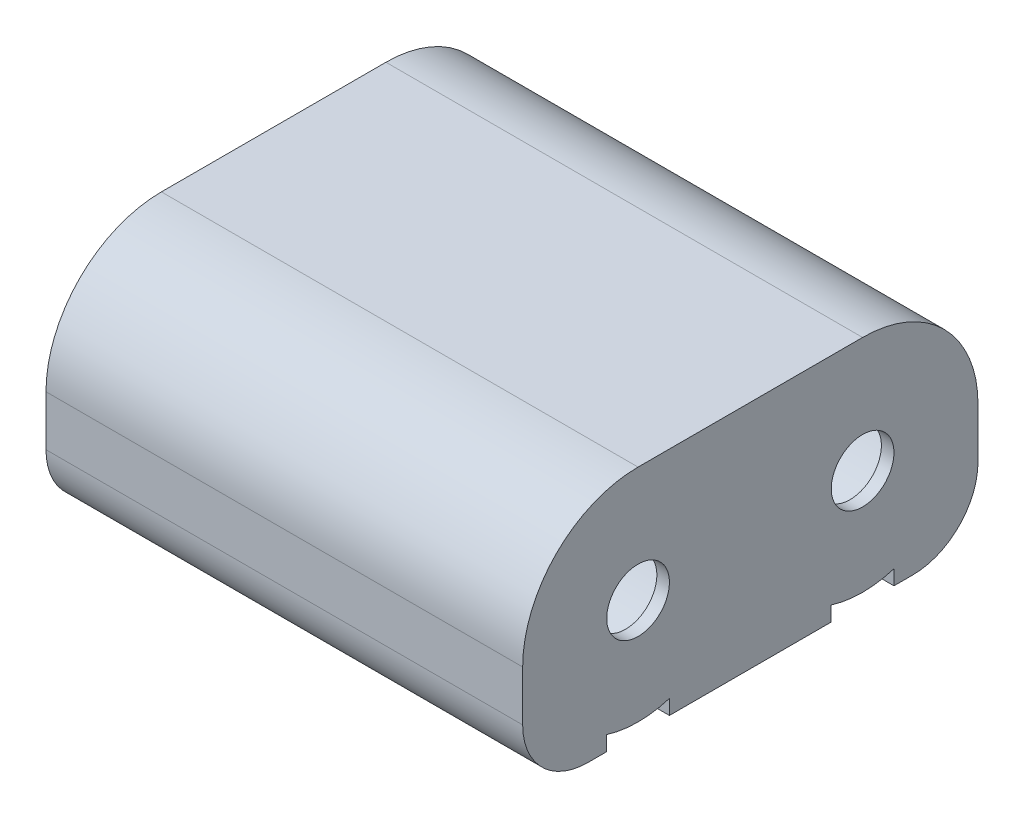
SolidWorks part; units mm, degrees
ref_plane "Спереди" through (0, 0, 0) normal (0, 0, 1) x (1, 0, 0)
ref_plane "Сверху" through (0, 0, 0) normal (0, 1, 0) x (1, 0, 0)
ref_plane "Справа" through (0, 0, 0) normal (1, 0, 0) x (0, 0, -1)
sketch "Эскиз1" plane through (0, 0, 0) normal (1, 0, 0) x (0, 0, -1)
  line L0 (0, -999.8279) -> (0, 49000.1721) construction
  line L1 (-1000, 0) -> (49000, 0) construction
  line L2 (-8.95, -9.2) -> (8.95, -9.2)
  line L3 (-8.95, -8.4) -> (-5.1977, -8.4) construction
  line L4 (-5.1977, -8.4) -> (-1.93, -8.4) construction
  line L5 (-1.93, -8.4) -> (1.93, -8.4)
  line L6 (5.1977, -8.4) -> (8.95, -8.4) construction
  line L7 (1.93, -8.4) -> (5.1977, -8.4) construction
  line L8 (-1.93, 8.4) -> (1.93, 8.4)
  line L9 (-8.95, 9.2) -> (8.95, 9.2)
  line L10 (-18.15, -4) -> (-18.15, 0)
  line L11 (18.15, -4) -> (18.15, 0)
  line L12 (12.95, -9.2) -> (8.95, -9.2)
  line L13 (-12.95, -9.2) -> (-8.95, -9.2)
  arc A2 (-1.93, -8.4) -> (-2.6183, -6.6745) centre (-1.93, -7.4) cw
  arc A3 (1.93, -8.4) -> (2.6183, -6.6745) centre (1.93, -7.4) ccw
  circle A14 centre (-8.95, 0) radius 8.35 construction
  circle A15 centre (-8.95, 0) radius 8.35 construction
  circle A16 centre (-8.95, 0) radius 8.4
  arc A17 (-2.6183, -6.6745) -> (-0.8775, -4.4129) centre (-8.95, 0) ccw
  circle A18 centre (8.95, 0) radius 8.35 construction
  circle A19 centre (8.95, 0) radius 8.35 construction
  circle A20 centre (8.95, 0) radius 8.4
  arc A21 (18.15, 0) -> (8.95, 9.2) centre (8.95, 0) ccw
  arc A22 (-5.1977, -8.4) -> (-2.6183, -6.6745) centre (-8.95, 0) ccw construction
  circle A23 centre (-8.95, 0) radius 9.2 construction
  arc A24 (-8.95, -9.2) -> (-5.1977, -8.4) centre (-8.95, 0) ccw construction
  arc A25 (5.1977, -8.4) -> (8.95, -9.2) centre (8.95, 0) ccw construction
  circle A26 centre (8.95, 0) radius 9.2 construction
  arc A27 (2.6183, -6.6745) -> (5.1977, -8.4) centre (8.95, 0) ccw construction
  arc A28 (-1.93, 8.4) -> (-2.6183, 6.6745) centre (-1.93, 7.4) ccw
  arc A29 (1.93, 8.4) -> (2.6183, 6.6745) centre (1.93, 7.4) cw
  arc A30 (-2.6183, 6.6745) -> (-8.95, 9.2) centre (-8.95, 0) ccw construction
  arc A31 (-8.95, 9.2) -> (-18.15, 0) centre (-8.95, 0) ccw
  arc A32 (8.95, 9.2) -> (2.6183, 6.6745) centre (8.95, 0) ccw construction
  arc A33 (2.6183, 6.6745) -> (0.8775, 4.4129) centre (8.95, 0) ccw
  arc A34 (0.8775, -4.4129) -> (-0.8775, -4.4129) centre (0, -4.8926) ccw
  arc A35 (0.8775, 4.4129) -> (-0.8775, 4.4129) centre (0, 4.8926) cw
  arc A36 (0, 2.1301) -> (-0.8775, 4.4129) centre (-8.95, 0) ccw construction
  arc A37 (-0.8775, 4.4129) -> (-2.6183, 6.6745) centre (-8.95, 0) ccw
  arc A38 (0.8775, 4.4129) -> (0, 2.1301) centre (8.95, 0) ccw construction
  arc A39 (0.8775, -4.4129) -> (2.6183, -6.6745) centre (8.95, 0) ccw
  arc A40 (0, 2.1301) -> (0.8775, -4.4129) centre (8.95, 0) ccw construction
  arc A41 (-0.8775, -4.4129) -> (0, 2.1301) centre (-8.95, 0) ccw construction
  arc A42 (-12.95, -9.2) -> (-18.15, -4) centre (-12.95, -4) cw
  arc A43 (12.95, -9.2) -> (18.15, -4) centre (12.95, -4) ccw
  arc A44 (-18.15, 0) -> (-8.95, -9.2) centre (-8.95, 0) ccw construction
  arc A45 (8.95, -9.2) -> (18.15, 0) centre (8.95, 0) ccw construction
  dimension "D3" = 4
  dimension "D5" = 1
  dimension "D1" = 0.05
  dimension "D2" = 0.8
extrude "Бобышка-Вытянуть1" add sketch "Эскиз1" along normal mid plane 37
sketch "Эскиз2" plane through (18.5, 0, 0) normal (1, 0, 0) x (0, 0, -1)
  line L4 (18.15, -4) -> (18.15, 0) construction
  line L5 (-12.95, -9.2) -> (12.95, -9.2) construction
  line L6 (-18.15, 0) -> (-18.15, -4) construction
  line L7 (8.95, 9.2) -> (-8.95, 9.2) construction
  line L8 (18.15, -4) -> (18.15, 0)
  line L9 (-12.95, -9.2) -> (12.95, -9.2)
  line L10 (-18.15, 0) -> (-18.15, -4)
  line L11 (8.95, 9.2) -> (-8.95, 9.2)
  circle A4 centre (-8.95, 0) radius 2.5
  circle A5 centre (8.95, 0) radius 2.5
  arc A7 (18.15, 0) -> (8.95, 9.2) centre (8.95, 0) ccw construction
  arc A8 (12.95, -9.2) -> (18.15, -4) centre (12.95, -4) ccw construction
  arc A9 (-18.15, -4) -> (-12.95, -9.2) centre (-12.95, -4) ccw construction
  arc A10 (-8.95, 9.2) -> (-18.15, 0) centre (-8.95, 0) ccw construction
  arc A11 (18.15, 0) -> (8.95, 9.2) centre (8.95, 0) ccw
  arc A12 (12.95, -9.2) -> (18.15, -4) centre (12.95, -4) ccw
  arc A13 (-18.15, -4) -> (-12.95, -9.2) centre (-12.95, -4) ccw
  arc A14 (-8.95, 9.2) -> (-18.15, 0) centre (-8.95, 0) ccw
  dimension "D1" = 5
extrude "Бобышка-Вытянуть2" add sketch "Эскиз2" along normal blind 1
sketch "Эскиз3" plane through (0, -9.2, 0) normal (0, -1, 0) x (1, 0, 0)
  line L0 (0, -1000) -> (0, 49000) construction
  line L1 (-1000, 0) -> (49000, 0) construction
  circle A0 centre (-10, 0) radius 1.5
  circle A1 centre (10, 0) radius 1.5
  dimension "D1" = 3
  dimension "D2" = 20
ref_plane "Плоскость1" through (-10, 0, 0) normal (1, 0, 0) x (0, 0, -1)
sketch "Эскиз5" plane through (-10, 0, 0) normal (1, 0, 0) x (0, 0, -1)
  line L1 (-1.93, -8.4) -> (1.93, -8.4)
  line L2 (-1.93, -8.4) -> (1.93, -8.4)
  arc A5 (-2.6183, -6.6745) -> (-1.93, -8.4) centre (-1.93, -7.4) ccw
  arc A6 (1.93, -8.4) -> (2.6183, -6.6745) centre (1.93, -7.4) ccw
  arc A7 (0.8775, -4.4129) -> (2.6183, -6.6745) centre (8.95, 0) ccw
  arc A8 (0.8775, -4.4129) -> (-0.8775, -4.4129) centre (0, -4.8926) ccw
  arc A9 (-2.6183, -6.6745) -> (-0.8775, -4.4129) centre (-8.95, 0) ccw
  arc A10 (-2.6183, -6.6745) -> (-1.93, -8.4) centre (-1.93, -7.4) ccw
  arc A11 (1.93, -8.4) -> (2.6183, -6.6745) centre (1.93, -7.4) ccw
  arc A12 (0.8775, -4.4129) -> (2.6183, -6.6745) centre (8.95, 0) ccw
  arc A13 (0.8775, -4.4129) -> (-0.8775, -4.4129) centre (0, -4.8926) ccw
  arc A14 (-2.6183, -6.6745) -> (-0.8775, -4.4129) centre (-8.95, 0) ccw
  dimension "D1" = 0
extrude "Бобышка-Вытянуть4" add sketch "Эскиз5" along normal mid plane 6
mirror "Зеркальное отражение1" about plane through (0, 0, 0) normal (1, 0, 0) of "Бобышка-Вытянуть4"
extrude "Вырез-Вытянуть1" cut sketch "Эскиз3" against normal blind 5
sketch "Эскиз6" plane through (-18.5, 0, 0) normal (-1, 0, 0) x (0, 0, 1)
  line L0 (10.45, -7.1953) -> (10.45, -16.35) construction
  line L1 (7.45, -16.35) -> (7.45, -7.1953) construction
  line L2 (-7.45, -7.1953) -> (-7.45, -16.35) construction
  line L3 (-10.45, -16.35) -> (-10.45, -7.1953) construction
  line L4 (10.45, -7.1953) -> (10.45, -8.265) construction
  line L5 (7.45, -8.265) -> (7.45, -7.1953) construction
  line L6 (-7.45, -8.265) -> (-7.45, -9.2) construction
  line L7 (-10.45, -9.2) -> (-10.45, -8.265) construction
  line L8 (12.95, -9.2) -> (-12.95, -9.2) construction
  line L9 (11.45, -9.2) -> (6.45, -9.2)
  line L10 (-7.45, -9.2) -> (-7.45, -16.35) construction
  line L11 (-10.45, -16.35) -> (-10.45, -9.2) construction
  line L12 (7.45, -16.35) -> (7.45, -9.2) construction
  line L13 (10.45, -9.2) -> (10.45, -16.35) construction
  line L14 (-6.45, -8.0194) -> (-6.45, -9.2)
  line L15 (-11.45, -9.2) -> (-11.45, -8.0194)
  line L16 (6.45, -9.2) -> (6.45, -8.0194)
  line L17 (11.45, -8.0194) -> (11.45, -9.2)
  line L18 (-11.45, -8.0194) -> (-11.45, -7.1953) construction
  line L19 (-11.45, -9.2) -> (-11.45, -7.1953) construction
  line L20 (-10.45, -8.265) -> (-10.45, -7.1953) construction
  line L21 (-10.45, -9.2) -> (-10.45, -7.1953) construction
  line L22 (-7.45, -7.1953) -> (-7.45, -8.265) construction
  line L23 (-7.45, -7.1953) -> (-7.45, -9.2) construction
  line L24 (-6.45, -7.1953) -> (-6.45, -8.0194) construction
  line L25 (-6.45, -7.1953) -> (-6.45, -9.2) construction
  line L26 (-11.45, -9.2) -> (-12.95, -9.2) construction
  line L27 (6.45, -9.2) -> (-6.45, -9.2) construction
  line L28 (-6.45, -9.2) -> (-11.45, -9.2)
  line L29 (12.95, -9.2) -> (11.45, -9.2) construction
  line L30 (10.45, -8.265) -> (10.45, -9.2) construction
  line L31 (10.45, -7.1953) -> (10.45, -9.2) construction
  line L32 (7.45, -9.2) -> (7.45, -8.265) construction
  line L33 (7.45, -9.2) -> (7.45, -7.1953) construction
  line L34 (11.45, -7.1953) -> (11.45, -8.0194) construction
  line L35 (11.45, -7.1953) -> (11.45, -9.2) construction
  line L36 (6.45, -8.0194) -> (6.45, -7.1953) construction
  line L37 (6.45, -9.2) -> (6.45, -7.1953) construction
  circle A0 centre (-8.95, 0) radius 8.4 construction
  arc A1 (-11.45, -8.0194) -> (-6.45, -8.0194) centre (-8.95, 0) ccw
  circle A2 centre (8.95, 0) radius 8.4 construction
  arc A3 (6.45, -8.0194) -> (11.45, -8.0194) centre (8.95, 0) ccw
  arc A4 (-6.45, -8.0194) -> (-11.45, -8.0194) centre (-8.95, 0) ccw construction
  arc A5 (11.45, -8.0194) -> (6.45, -8.0194) centre (8.95, 0) ccw construction
  dimension "D1" = 1
extrude "Вырез-Вытянуть2" cut sketch "Эскиз6" against normal blind 2
sketch "Эскиз7" plane through (19.5, 0, 0) normal (1, 0, 0) x (0, 0, -1)
  line L0 (-6.45, -8.0194) -> (-6.45, -9.2) construction
  line L1 (-6.45, -9.2) -> (-11.45, -9.2) construction
  line L2 (-11.45, -9.2) -> (-11.45, -8.0194) construction
  line L3 (11.45, -9.2) -> (6.45, -9.2) construction
  line L4 (6.45, -9.2) -> (6.45, -8.0194) construction
  line L5 (11.45, -8.0194) -> (11.45, -9.2) construction
  line L6 (-6.45, -8.0194) -> (-6.45, -9.2)
  line L7 (-6.45, -9.2) -> (-11.45, -9.2)
  line L8 (-11.45, -9.2) -> (-11.45, -8.0194)
  line L9 (11.45, -9.2) -> (6.45, -9.2)
  line L10 (6.45, -9.2) -> (6.45, -8.0194)
  line L11 (11.45, -8.0194) -> (11.45, -9.2)
  arc A0 (-11.45, -8.0194) -> (-6.45, -8.0194) centre (-8.95, 0) ccw construction
  arc A1 (6.45, -8.0194) -> (11.45, -8.0194) centre (8.95, 0) ccw construction
  arc A2 (-11.45, -8.0194) -> (-6.45, -8.0194) centre (-8.95, 0) ccw
  arc A3 (6.45, -8.0194) -> (11.45, -8.0194) centre (8.95, 0) ccw
extrude "Вырез-Вытянуть3" cut sketch "Эскиз7" against normal blind 3
